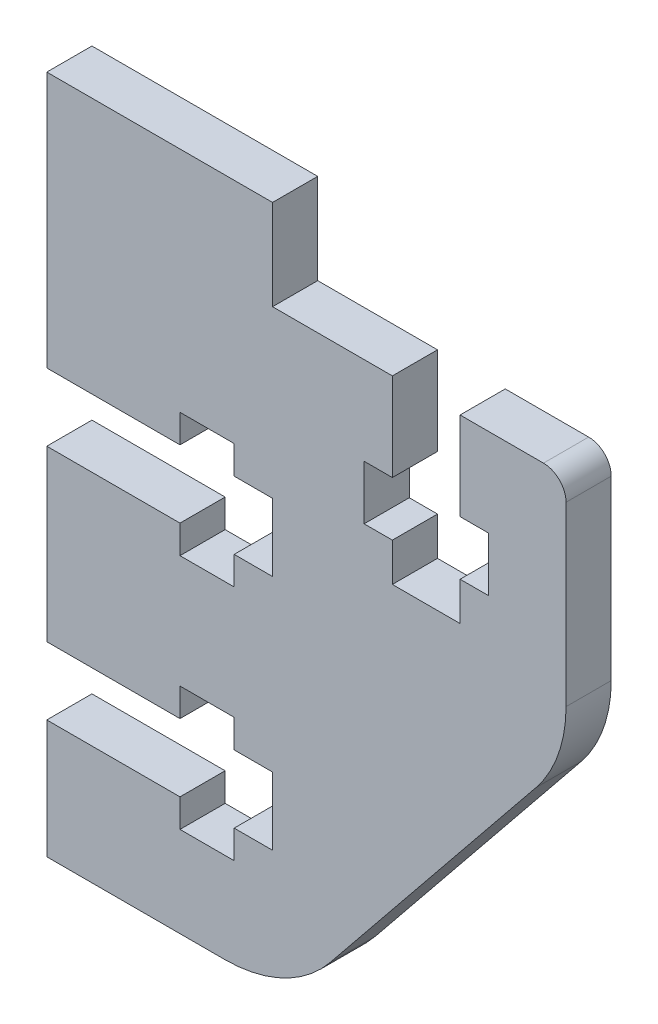
SolidWorks part; units mm, degrees
material "Acrylic (Medium-high impact)"
ref_plane "Front Plane" through (0, 0, 0) normal (0, 0, 1) x (1, 0, 0)
ref_plane "Top Plane" through (0, 0, 0) normal (0, 1, 0) x (1, 0, 0)
ref_plane "Right Plane" through (0, 0, 0) normal (1, 0, 0) x (0, 0, -1)
sketch "Model" plane through (0, 0, 0) normal (0, 0, 1) x (1, 0, 0)
  line L313 (2144.9422, 1193.4486) -> (2143.2422, 1193.4486)
  line L314 (2144.9422, 1196.4486) -> (2143.2422, 1196.4486)
  line L315 (2140.8422, 1196.4486) -> (2134.9422, 1196.4486)
  line L316 (2140.8422, 1193.4486) -> (2134.9422, 1193.4486)
  line L317 (2144.9422, 1193.4486) -> (2144.9422, 1196.4486)
  line L318 (2144.9422, 1214.2986) -> (2150.2482, 1214.2986)
  line L319 (2153.2482, 1214.2986) -> (2156.9422, 1214.2986)
  line L320 (2156.6064, 1201.6839) -> (2147.4949, 1190.4243)
  line L321 (2157.9422, 1213.2986) -> (2157.9422, 1205.4583)
  line L322 (2134.9422, 1188.1986) -> (2142.8307, 1188.1986)
  line L323 (2143.2422, 1192.1986) -> (2143.2422, 1193.4486)
  line L324 (2143.2422, 1196.4486) -> (2143.2422, 1197.6986)
  line L325 (2140.8422, 1192.1986) -> (2140.8422, 1193.4486)
  line L326 (2140.8422, 1196.4486) -> (2140.8422, 1197.6986)
  line L327 (2143.2422, 1192.1986) -> (2140.8422, 1192.1986)
  line L328 (2143.2422, 1197.6986) -> (2140.8422, 1197.6986)
  line L329 (2144.9422, 1203.9486) -> (2143.2422, 1203.9486)
  line L330 (2144.9422, 1206.9486) -> (2143.2422, 1206.9486)
  line L331 (2140.8422, 1206.9486) -> (2134.9422, 1206.9486)
  line L332 (2140.8422, 1203.9486) -> (2134.9422, 1203.9486)
  line L333 (2144.9422, 1203.9486) -> (2144.9422, 1206.9486)
  line L334 (2143.2422, 1202.6986) -> (2143.2422, 1203.9486)
  line L335 (2143.2422, 1206.9486) -> (2143.2422, 1208.1986)
  line L336 (2140.8422, 1202.6986) -> (2140.8422, 1203.9486)
  line L337 (2140.8422, 1206.9486) -> (2140.8422, 1208.1986)
  line L338 (2143.2422, 1202.6986) -> (2140.8422, 1202.6986)
  line L339 (2143.2422, 1208.1986) -> (2140.8422, 1208.1986)
  line L340 (2150.2482, 1206.2986) -> (2150.2482, 1207.9986)
  line L341 (2153.2482, 1206.2986) -> (2153.2482, 1207.9986)
  line L342 (2153.2482, 1210.3986) -> (2153.2482, 1214.2986)
  line L343 (2150.2482, 1210.3986) -> (2150.2482, 1214.2986)
  line L344 (2150.2482, 1206.2986) -> (2153.2482, 1206.2986)
  line L345 (2148.9982, 1207.9986) -> (2150.2482, 1207.9986)
  line L346 (2153.2482, 1207.9986) -> (2154.4982, 1207.9986)
  line L347 (2148.9982, 1210.3986) -> (2150.2482, 1210.3986)
  line L348 (2153.2482, 1210.3986) -> (2154.4982, 1210.3986)
  line L349 (2148.9982, 1207.9986) -> (2148.9982, 1210.3986)
  line L350 (2154.4982, 1207.9986) -> (2154.4982, 1210.3986)
  line L351 (2144.9422, 1218.2986) -> (2134.9422, 1218.2986)
  line L352 (2134.9422, 1188.1986) -> (2134.9422, 1193.4486)
  line L353 (2134.9422, 1196.4486) -> (2134.9422, 1203.9486)
  line L354 (2134.9422, 1206.9486) -> (2134.9422, 1218.2986)
  line L581 (2144.9422, 1214.2986) -> (2144.9422, 1218.2986)
  arc A138 (2157.9422, 1213.2986) -> (2156.9422, 1214.2986) centre (2156.9422, 1213.2986) ccw
  arc A139 (2156.6064, 1201.6839) -> (2157.9422, 1205.4583) centre (2151.9422, 1205.4583) ccw
  arc A140 (2142.8307, 1188.1986) -> (2147.4949, 1190.4243) centre (2142.8307, 1194.1986) ccw
extrude "Boss-Extrude1" add sketch "Model" along normal blind 2
